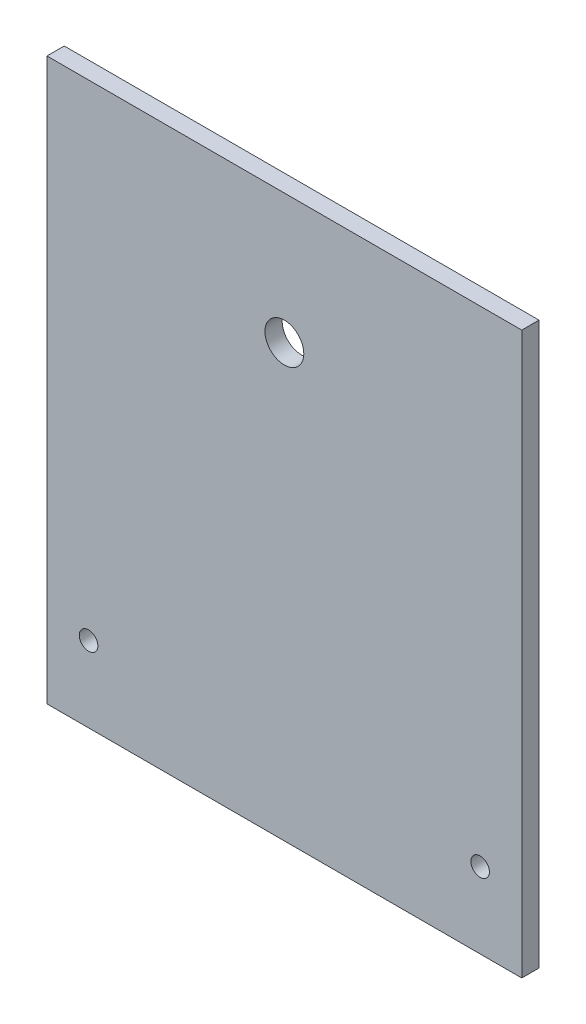
SolidWorks part; units mm, degrees
ref_plane "Front Plane" through (0, 0, 0) normal (0, 0, 1) x (1, 0, 0)
ref_plane "Top Plane" through (0, 0, 0) normal (0, 1, 0) x (1, 0, 0)
ref_plane "Right Plane" through (0, 0, 0) normal (1, 0, 0) x (0, 0, -1)
sketch "Sketch1" plane through (0, 0, 0) normal (0, 0, 1) x (1, 0, 0)
  line L1 (-55, 65) -> (55, 65)
  line L2 (-55, 65) -> (-55, -65)
  line L3 (-55, -65) -> (55, -65)
  line L4 (55, 65) -> (55, -65)
  line L5 (-55, 65) -> (55, -65) construction
  line L6 (-55, -65) -> (55, 65) construction
  point P0 (0, 0)
  dimension "D1" = 110
  dimension "D2" = 130
extrude "Boss-Extrude1" add sketch "Sketch1" along normal blind 4
sketch "Sketch2" plane through (0, 0, 4) normal (0, 0, 1) x (1, 0, 0)
  line L0 (0, 0) -> (0, 65) construction
  line L1 (55, 65) -> (-55, 65) construction
  line L2 (0, 0) -> (0, -65) construction
  line L3 (-55, -65) -> (55, -65) construction
  line L4 (-12.8508, 34.9933) -> (15.998, 34.9933) construction
  line L5 (18.0961, 55.2062) -> (6.5566, 65) construction
  line L6 (6.5566, 65) -> (6.5566, 35) construction
  circle A0 centre (0, 34.9933) radius 4.5
  dimension "D1" = 30
extrude "Cut-Extrude1" cut sketch "Sketch2" against normal blind 4
sketch "Sketch3" plane through (0, 0, 4) normal (0, 0, 1) x (1, 0, 0)
  line L0 (0, 0) -> (0, -65) construction
  line L1 (-55, -65) -> (55, -65) construction
  line L2 (0, 34.9933) -> (55, -65) construction
  line L3 (0, 34.9933) -> (-55, -65) construction
sketch "Sketch4" plane through (0, 0, 4) normal (0, 0, 1) x (1, 0, 0)
  line L0 (-55, -65) -> (-45.3611, -47.476) construction
  line L1 (0, 34.9933) -> (-55, -65) construction
  circle A0 centre (-45.3611, -47.476) radius 2.15
  dimension "D1" = 20
extrude "Cut-Extrude2" cut sketch "Sketch4" against normal through all
sketch "Sketch5" plane through (0, 0, 4) normal (0, 0, 1) x (1, 0, 0)
  line L0 (55, -65) -> (45.3611, -47.476) construction
  line L1 (0, 34.9933) -> (55, -65) construction
  circle A0 centre (45.3611, -47.476) radius 2.15
  dimension "D1" = 20
extrude "Cut-Extrude3" cut sketch "Sketch5" against normal through all
